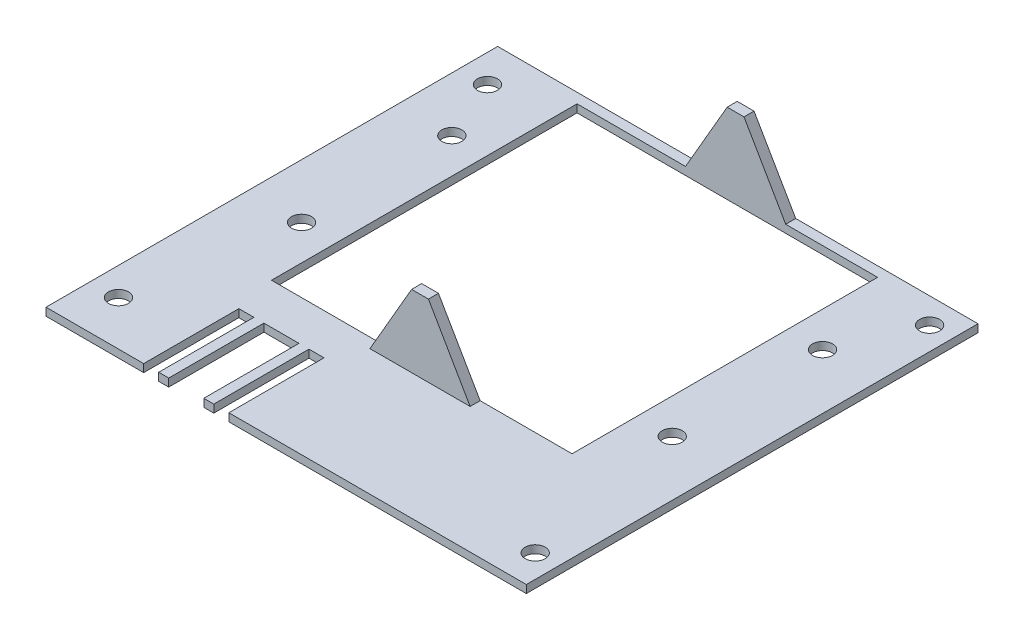
SolidWorks part; units mm, degrees
material "ABS"
ref_plane "Front Plane" through (0, 0, 0) normal (0, 0, 1) x (1, 0, 0)
ref_plane "Top Plane" through (0, 0, 0) normal (0, 1, 0) x (1, 0, 0)
ref_plane "Right Plane" through (0, 0, 0) normal (1, 0, 0) x (0, 0, -1)
sketch "Sketch1" plane through (0, 0, 0) normal (0, 1, 0) x (1, 0, 0)
  line L1 (-32.2441, 108.719) -> (64.6459, 108.719)
  line L2 (-32.2441, 108.719) -> (-32.2441, 18.549)
  line L3 (-32.2441, 18.549) -> (64.6459, 18.549)
  line L4 (64.6459, 108.719) -> (64.6459, 18.549)
  dimension "D1" = 96.89
  dimension "D2" = 90.17
extrude "PCB" add sketch "Sketch1" along normal blind 1.57
sketch "Sketch2" plane through (0, 1.57, 0) normal (0, 1, 0) x (1, 0, 0)
  line L0 (64.6459, 18.549) -> (64.6459, 108.719) construction
  line L1 (-32.2441, 18.549) -> (64.6459, 18.549) construction
  circle A0 centre (59.5659, 24.899) radius 2
  circle A1 centre (-26.1641, 27.439) radius 2
  circle A2 centre (-26.1641, 101.099) radius 2
  circle A3 centre (59.5659, 103.639) radius 2
  dimension "D3" = 4
  dimension "D6" = 4
  dimension "D11" = 4
  dimension "D12" = 4
  dimension "D1" = 5.08
  dimension "D2" = 6.35
  dimension "D4" = 90.81
  dimension "D5" = 8.89
  dimension "D7" = 90.81
  dimension "D8" = 5.08
  dimension "D9" = 85.09
  dimension "D10" = 82.55
extrude "M3 Mounting Holes" cut sketch "Sketch2" against normal blind 1.57
sketch "Sketch3" plane through (0, 1.57, 0) normal (0, 1, 0) x (1, 0, 0)
  line L0 (64.6459, 108.719) -> (-32.2441, 108.719) construction
  line L1 (12.7559, 108.719) -> (22.7559, 108.719)
  line L2 (12.7559, 108.719) -> (12.7559, 106.719)
  line L3 (12.7559, 106.719) -> (22.7559, 106.719)
  line L4 (22.7559, 108.719) -> (22.7559, 106.719)
  line L5 (-32.2441, 108.719) -> (-32.2441, 18.549) construction
  line L7 (12.7559, 45.719) -> (22.7559, 45.719)
  line L8 (12.7559, 45.719) -> (12.7559, 43.719)
  line L9 (12.7559, 43.719) -> (22.7559, 43.719)
  line L10 (22.7559, 45.719) -> (22.7559, 43.719)
  dimension "D1" = 2
  dimension "D2" = 10
  dimension "D3" = 0
  dimension "D4" = 45
  dimension "D5" = 61
  dimension "D6" = 2
  dimension "D7" = 45
extrude "Boss-Extrude1" [suppressed] add sketch "Sketch3" along normal blind 10
sketch "Sketch4" plane through (0, 1.57, 0) normal (0, 1, 0) x (1, 0, 0)
  line L0 (64.6459, 108.719) -> (-32.2441, 108.719) construction
  line L1 (64.6459, 108.719) -> (-32.2441, 108.719) construction
  line L2 (-32.2441, 108.719) -> (-32.2441, 18.549) construction
  line L3 (64.6459, 108.719) -> (-32.2441, 108.719) construction
  circle A0 centre (-20.8941, 88.719) radius 2
  circle A1 centre (53.1059, 88.719) radius 2
  circle A2 centre (-20.8941, 58.719) radius 2
  circle A3 centre (53.1059, 58.719) radius 2
  dimension "D1" = 4
  dimension "D2" = 4
  dimension "D7" = 4
  dimension "D8" = 4
  dimension "D12" = 74
  dimension "D3" = 20
  dimension "D4" = 20
  dimension "D5" = 74
  dimension "D6" = 11.35
  dimension "D9" = 50
  dimension "D10" = 50
  dimension "D11" = 11.35
extrude "Cut-Extrude1" cut sketch "Sketch4" against normal blind 23
ref_plane "Plane1" through (0, 0, -45.719) normal (0, 0, 1) x (1, 0, 0)
sketch "Sketch7" plane through (0, 0, -45.719) normal (0, 0, 1) x (1, 0, 0)
  line L0 (27.7559, 1.57) -> (19.4384, 15.9764)
  line L1 (19.4384, 15.9764) -> (16.0735, 15.9764)
  line L2 (16.0735, 15.9764) -> (7.7559, 1.57)
  line L3 (7.7559, 1.57) -> (27.7559, 1.57)
  line L4 (-32.2441, 1.57) -> (64.6459, 1.57) construction
  dimension "D1" = 60
  dimension "D2" = 60
  dimension "D3" = 0
  dimension "D4" = 3.3649
  dimension "D5" = 20
  dimension "D6" = 5
ref_plane "Plane2" through (0, 0, -108.719) normal (0, 0, 1) x (1, 0, 0)
sketch "Sketch8" plane through (0, 0, -108.719) normal (0, 0, 1) x (1, 0, 0)
  line L0 (27.7559, 1.57) -> (19.4384, 15.9764) construction
  line L1 (19.4384, 15.9764) -> (16.0735, 15.9764) construction
  line L2 (16.0735, 15.9764) -> (7.7559, 1.57) construction
  line L3 (7.7559, 1.57) -> (27.7559, 1.57) construction
  line L4 (27.7559, 1.57) -> (19.4384, 15.9764)
  line L5 (19.4384, 15.9764) -> (16.0735, 15.9764)
  line L6 (16.0735, 15.9764) -> (7.7559, 1.57)
  line L7 (7.7559, 1.57) -> (27.7559, 1.57)
extrude "Boss-Extrude2" add sketch "Sketch7" along normal blind 2
extrude "Boss-Extrude3" add sketch "Sketch8" along normal blind 2
sketch "Sketch9" plane through (0, 1.57, 0) normal (0, 1, 0) x (1, 0, 0)
  line L0 (-32.2441, 18.549) -> (64.6459, 18.549) construction
  line L1 (-9.2441, 18.549) -> (-12.2441, 18.549)
  line L2 (-9.2441, 18.549) -> (-9.2441, 37.549)
  line L3 (-9.2441, 37.549) -> (-12.2441, 37.549)
  line L4 (-12.2441, 18.549) -> (-12.2441, 37.549)
  line L5 (-32.2441, 108.719) -> (-32.2441, 18.549) construction
  line L6 (-7.2441, 18.549) -> (-0.2441, 18.549)
  line L7 (-7.2441, 18.549) -> (-7.2441, 37.549)
  line L8 (-7.2441, 37.549) -> (-0.2441, 37.549)
  line L9 (-0.2441, 18.549) -> (-0.2441, 37.549)
  line L11 (1.7559, 18.549) -> (4.7559, 18.549)
  line L12 (1.7559, 18.549) -> (1.7559, 37.549)
  line L13 (1.7559, 37.549) -> (4.7559, 37.549)
  line L14 (4.7559, 18.549) -> (4.7559, 37.549)
  dimension "D1" = 19
  dimension "D2" = 19
  dimension "D3" = 2
  dimension "D4" = 3
  dimension "D5" = 7
  dimension "D6" = 20
  dimension "D7" = 3
  dimension "D8" = 19
  dimension "D9" = 2
extrude "Cut-Extrude2" cut sketch "Sketch9" against normal through all
sketch "Sketch10" plane through (0, 1.57, 0) normal (0, 1, 0) x (1, 0, 0)
  line L0 (7.7559, 108.719) -> (-32.2441, 108.719) construction
  line L1 (-32.2441, 18.549) -> (-31.7441, 18.549)
  line L2 (-32.2441, 18.549) -> (-32.2441, 108.719)
  line L3 (-32.2441, 108.719) -> (-31.7441, 108.719)
  line L4 (-31.7441, 18.549) -> (-31.7441, 108.719)
  line L5 (64.6459, 108.719) -> (27.7559, 108.719) construction
  line L6 (64.6459, 18.549) -> (64.1459, 18.549)
  line L7 (64.6459, 18.549) -> (64.6459, 108.719)
  line L8 (64.6459, 108.719) -> (64.1459, 108.719)
  line L9 (64.1459, 18.549) -> (64.1459, 108.719)
  dimension "D1" = 0.5
  dimension "D2" = 0.5
extrude "Cut-Extrude3" cut sketch "Sketch10" against normal blind 10
sketch "Sketch11" plane through (0, 1.57, 0) normal (0, 1, 0) x (1, 0, 0)
  line L0 (7.7559, 106.719) -> (27.7559, 106.719) construction
  line L1 (-13.8941, 106.719) -> (46.1059, 106.719)
  line L2 (-13.8941, 106.719) -> (-13.8941, 45.719)
  line L3 (-13.8941, 45.719) -> (46.1059, 45.719)
  line L4 (46.1059, 106.719) -> (46.1059, 45.719)
  dimension "D1" = 60
  dimension "D2" = 61
  dimension "D3" = 0
  dimension "D4" = 7
extrude "Cut-Extrude4" cut sketch "Sketch11" against normal blind 10
